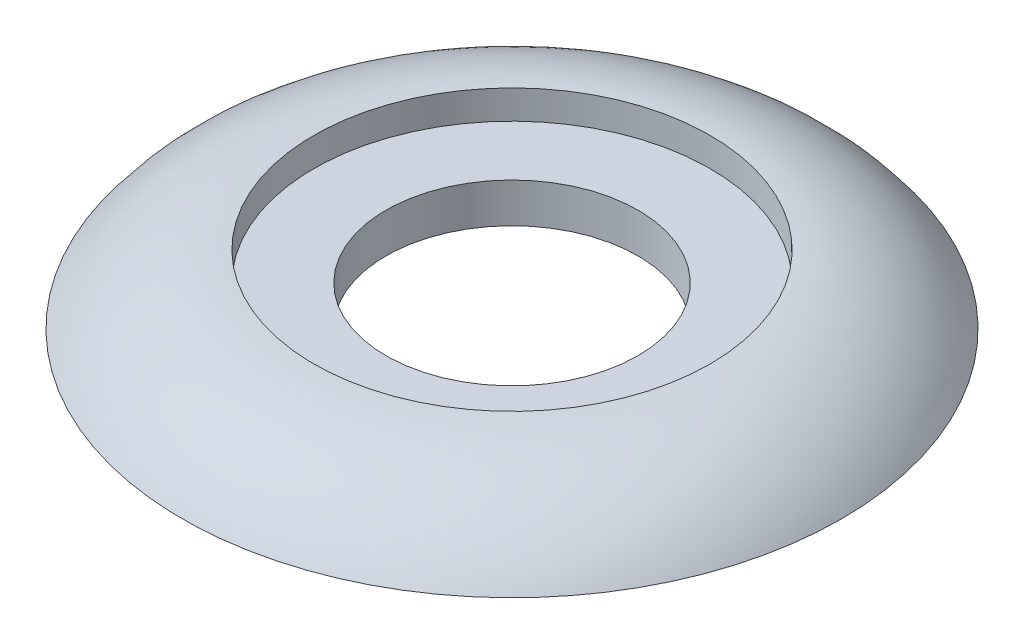
SolidWorks part; units mm, degrees
material "PET"
ref_plane "Front Plane" through (0, 0, 0) normal (0, 0, 1) x (1, 0, 0)
ref_plane "Top Plane" through (0, 0, 0) normal (0, 1, 0) x (1, 0, 0)
ref_plane "Right Plane" through (0, 0, 0) normal (1, 0, 0) x (0, 0, -1)
sketch "Sketch1" plane through (0, 0, 0) normal (0, 0, 1) x (1, 0, 0)
  line L0 (0, -397.3824) -> (0, 19471.7391) construction
  line L1 (0, 0) -> (4.445, 0) construction
  line L2 (4.445, 0) -> (11.6205, 0)
  line L3 (4.445, 0) -> (4.445, 1.397)
  line L4 (4.445, 1.397) -> (6.985, 1.397)
  line L5 (6.985, 1.397) -> (6.985, 2.413)
  arc A0 (6.985, 2.413) -> (11.6205, 0) centre (6.985, -3.246) cw
  dimension "D1" = 4.445
  dimension "D2" = 11.6205
  dimension "D3" = 1.016
  dimension "D4" = 1.397
  dimension "D5" = 2.54
revolve "Revolve1" add sketch "Sketch1" angle 360 about L0
